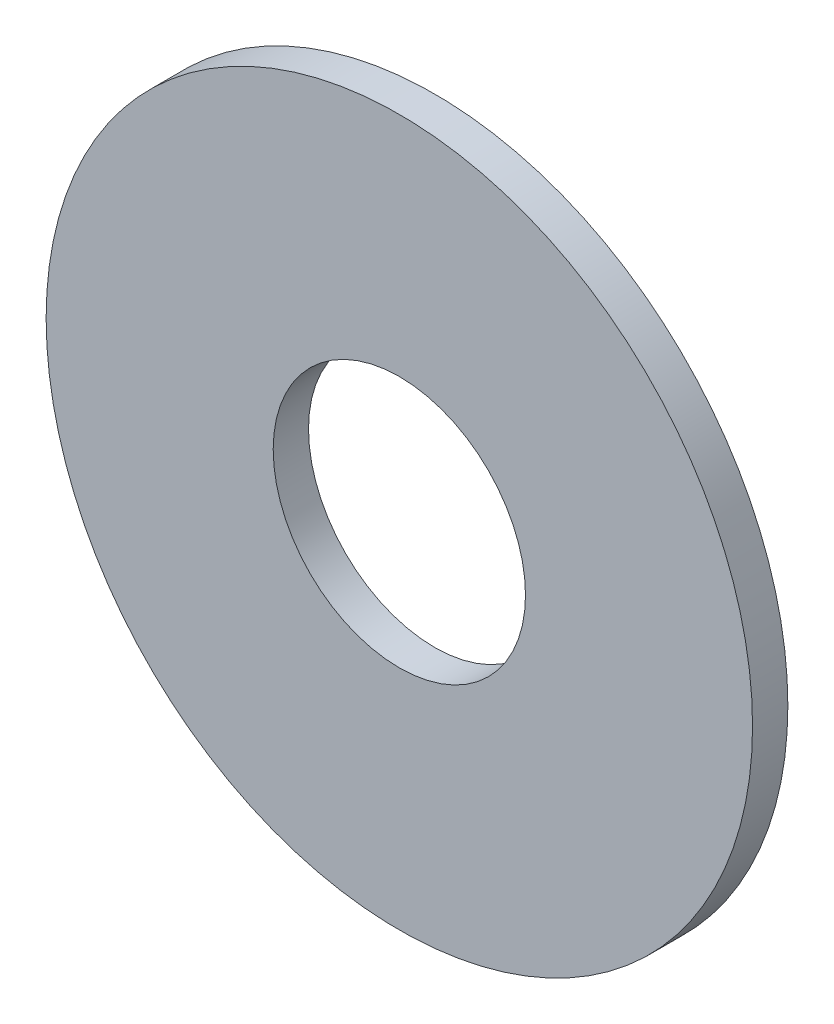
SolidWorks part; units mm, degrees
ref_plane "Plan de face" through (0, 0, 0) normal (0, 0, 1) x (1, 0, 0)
ref_plane "Plan de dessus" through (0, 0, 0) normal (0, 1, 0) x (1, 0, 0)
ref_plane "Plan de droite" through (0, 0, 0) normal (1, 0, 0) x (0, 0, -1)
sketch "Esquisse1" plane through (0, 0, 0) normal (0, 0, 1) x (1, 0, 0)
  circle A0 centre (0, 0) radius 7
extrude "Boss.-Extru.1" add sketch "Esquisse1" along normal blind 0.7
sketch "Esquisse2" plane through (0, 0, 0.7) normal (0, 0, 1) x (1, 0, 0)
  circle A0 centre (0, 0) radius 2.5
extrude "Enlèv. mat.-Extru.1" cut sketch "Esquisse2" against normal blind 1.5
